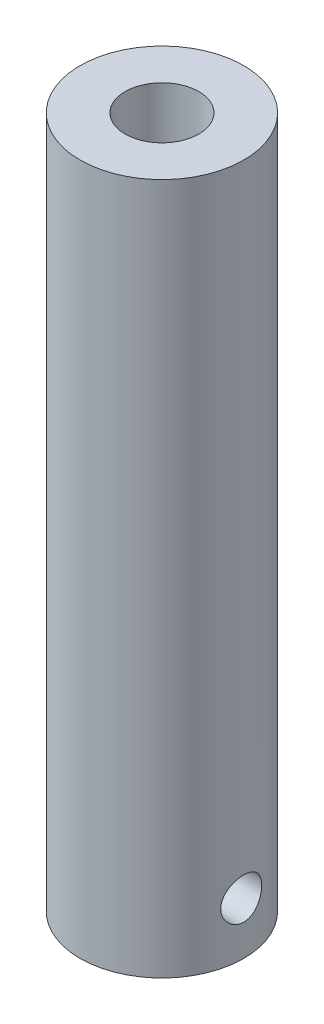
SolidWorks part; units mm, degrees
ref_plane "Front Plane" through (0, 0, 0) normal (0, 0, 1) x (1, 0, 0)
ref_plane "Top Plane" through (0, 0, 0) normal (0, 1, 0) x (1, 0, 0)
ref_plane "Right Plane" through (0, 0, 0) normal (1, 0, 0) x (0, 0, -1)
sketch "Szkic1" plane through (0, 0, 0) normal (0, 1, 0) x (1, 0, 0)
  circle A0 centre (0, 0) radius 2
  dimension "D1" = 4
extrude "Dodanie-wyciągnięcie1" add sketch "Szkic1" along normal blind 16.9
ref_plane "Płaszczyzna1" through (0, 16.9, 0) normal (0, 1, 0) x (1, 0, 0)
sketch "Szkic2" plane through (0, 16.9, 0) normal (0, 1, 0) x (1, 0, 0)
  circle A0 centre (0, 0) radius 0.9
  dimension "D1" = 1.8
extrude "Wytnij-wyciągnięcie1" cut sketch "Szkic2" against normal blind 10
sketch "Szkic3" plane through (0, 0, 0) normal (1, 0, 0) x (0, 0, -1)
  circle A0 centre (0, 1.2689) radius 0.5
  point P2 (0, 1.8058)
  point P3 (0, 1.2689)
  dimension "D1" = 1
extrude "Wytnij-wyciągnięcie2" cut sketch "Szkic3" against normal through all both and the other way through all
